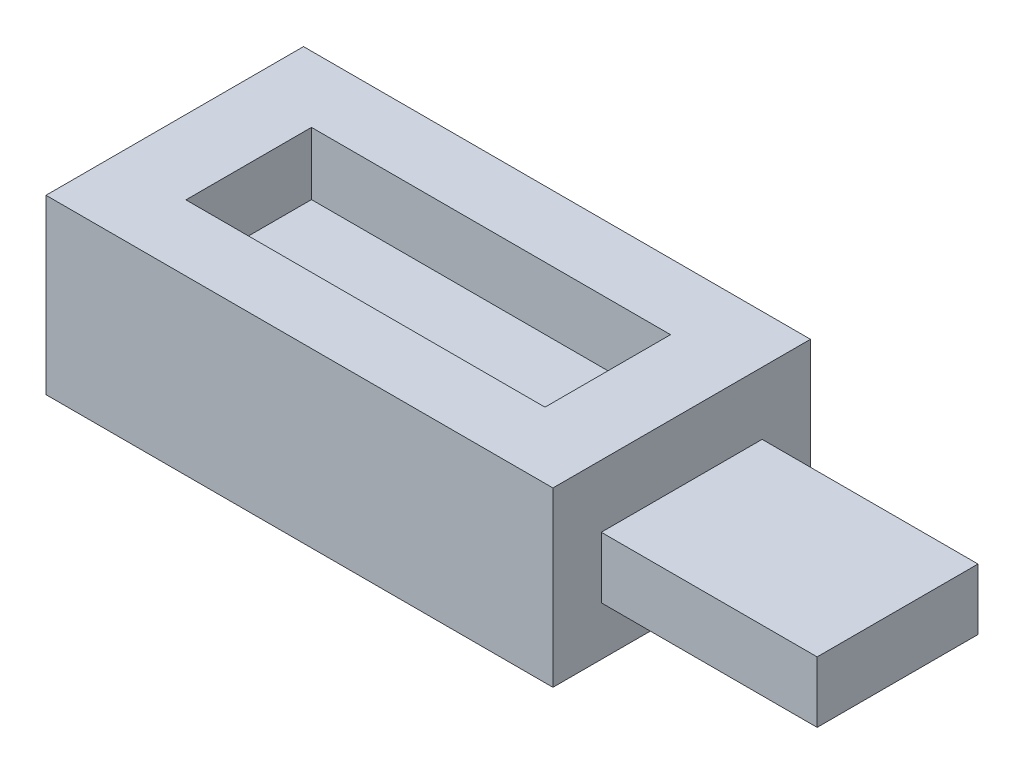
SolidWorks part; units mm, degrees
ref_plane "Front Plane" through (0, 0, 0) normal (0, 0, 1) x (1, 0, 0)
ref_plane "Top Plane" through (0, 0, 0) normal (0, 1, 0) x (1, 0, 0)
ref_plane "Right Plane" through (0, 0, 0) normal (1, 0, 0) x (0, 0, -1)
sketch "Sketch1" plane through (0, 0, 0) normal (0, 1, 0) x (1, 0, 0)
  line L1 (-102.8928, -52.2674) -> (102.8928, -52.2674)
  line L2 (-102.8928, -52.2674) -> (-102.8928, 52.2674)
  line L3 (-102.8928, 52.2674) -> (102.8928, 52.2674)
  line L4 (102.8928, -52.2674) -> (102.8928, 52.2674)
  line L5 (-102.8928, -52.2674) -> (102.8928, 52.2674) construction
  line L6 (-102.8928, 52.2674) -> (102.8928, -52.2674) construction
  point P0 (0, 0)
extrude "Boss-Extrude1" add sketch "Sketch1" along normal blind 70.104
sketch "Sketch2" plane through (0, 70.104, 0) normal (0, 1, 0) x (1, 0, 0)
  line L1 (-72.8794, -25.487) -> (72.8794, -25.487)
  line L2 (-72.8794, -25.487) -> (-72.8794, 25.487)
  line L3 (-72.8794, 25.487) -> (72.8794, 25.487)
  line L4 (72.8794, -25.487) -> (72.8794, 25.487)
  line L5 (-72.8794, -25.487) -> (72.8794, 25.487) construction
  line L6 (-72.8794, 25.487) -> (72.8794, -25.487) construction
  point P0 (0, 0)
extrude "Cut-Extrude1" cut sketch "Sketch2" against normal blind 25.4
sketch "Sketch3" plane through (102.8928, 0, 0) normal (1, 0, 0) x (0, 0, -1)
  line L1 (-32.6491, 19.9219) -> (32.6491, 19.9219)
  line L2 (-32.6491, 19.9219) -> (-32.6491, 44.7216)
  line L3 (-32.6491, 44.7216) -> (32.6491, 44.7216)
  line L4 (32.6491, 19.9219) -> (32.6491, 44.7216)
  line L5 (-32.6491, 19.9219) -> (32.6491, 44.7216) construction
  line L6 (-32.6491, 44.7216) -> (32.6491, 19.9219) construction
  point P0 (0, 32.3218)
extrude "Boss-Extrude2" add sketch "Sketch3" along normal blind 87.63
sketch "Sketch4" plane through (0, 0, 52.2674) normal (0, 0, 1) x (1, 0, 0)
  line L0 (190.5228, 32.3218) -> (-126.4612, 32.3218)
  line L1 (190.5228, 44.7216) -> (190.5228, 19.9219) construction
  point P2 (192.1722, 31.9372)
  point P3 (190.5228, 32.3218)
